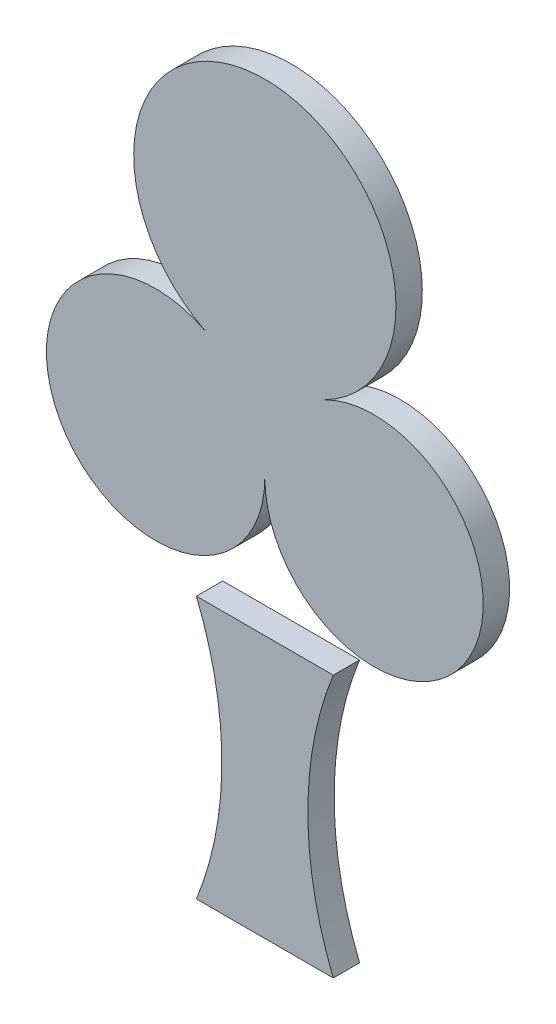
SolidWorks part; units mm, degrees
ref_plane "Front Plane" through (0, 0, 0) normal (0, 0, 1) x (1, 0, 0)
ref_plane "Top Plane" through (0, 0, 0) normal (0, 1, 0) x (1, 0, 0)
ref_plane "Right Plane" through (0, 0, 0) normal (1, 0, 0) x (0, 0, -1)
sketch "Sketch1" plane through (0, 0, 0) normal (0, 0, 1) x (1, 0, 0)
  line L0 (-451.4315, 0) -> (22120.1414, 0) construction
  line L1 (0, -451.4315) -> (0, 22120.1414) construction
  line L2 (-7.8, 14.95) -> (7.8, 14.95)
  line L3 (-7.8, -14.95) -> (7.8, -14.95)
  arc A0 (-7.8, 14.95) -> (-7.8, -14.95) centre (-44.8849, 0) cw
  arc A1 (7.8, 14.95) -> (7.8, -14.95) centre (44.8849, 0) ccw
  circle A2 centre (0, 54.95) radius 14.95
  circle A3 centre (12.45, 30.5419) radius 12.45
  circle A4 centre (-12.45, 30.5419) radius 12.45
  point P8 (-4.9, 0)
  dimension "D3" = 2.9
  dimension "D4" = 14.95
  dimension "D5" = 29.9
  dimension "D6" = 24.9
  dimension "D7" = 24.9
  dimension "D8" = 40
  dimension "D1" = 29.9
  dimension "D2" = 4.9
extrude "Boss-Extrude2" add sketch "Sketch1" along normal blind 3 contours A4 A3 A2 | A4 | A2 | A3 | A1 L2 A0 L3
